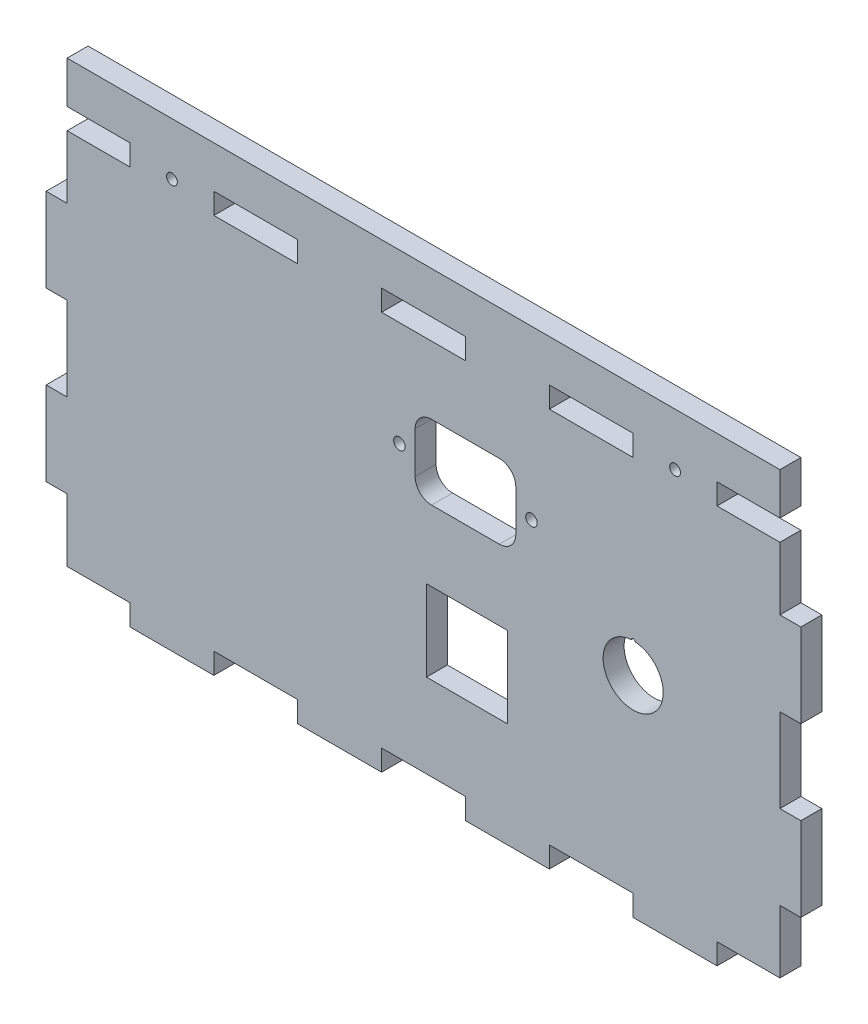
SolidWorks part; units mm, degrees
ref_plane "Front Plane" through (0, 0, 0) normal (0, 0, 1) x (1, 0, 0)
ref_plane "Top Plane" through (0, 0, 0) normal (0, 1, 0) x (1, 0, 0)
ref_plane "Right Plane" through (0, 0, 0) normal (1, 0, 0) x (0, 0, -1)
sketch "Sketch1" plane through (0, 0, 0) normal (0, 0, 1) x (1, 0, 0)
  line L1 (0, 0) -> (228.6, 0)
  line L2 (0, 0) -> (0, 139.7)
  line L3 (0, 139.7) -> (228.6, 139.7)
  line L4 (228.6, 0) -> (228.6, 139.7)
  dimension "D1" = 228.6
  dimension "D2" = 139.7
extrude "Boss-Extrude1" add sketch "Sketch1" along normal blind 6.35
sketch "Sketch5" plane through (0, 0, 6.35) normal (0, 0, 1) x (1, 0, 0)
  line L1 (0, 0) -> (6.35, 0)
  line L2 (0, 0) -> (0, 25.4)
  line L3 (0, 25.4) -> (6.35, 25.4)
  line L4 (6.35, 0) -> (6.35, 25.4)
  dimension "D1" = 25.4
  dimension "D2" = 6.35
extrude "Cut-Extrude4" cut sketch "Sketch5" against normal blind 6.35
sketch "Sketch6" plane through (0, 0, 6.35) normal (0, 0, 1) x (1, 0, 0)
  line L1 (0, 0) -> (25.4, 0)
  line L2 (0, 0) -> (0, 6.35)
  line L3 (0, 6.35) -> (25.4, 6.35)
  line L4 (25.4, 0) -> (25.4, 6.35)
  dimension "D1" = 6.35
  dimension "D2" = 25.4
extrude "Cut-Extrude5" cut sketch "Sketch6" against normal blind 6.35
pattern_linear "LPattern5" count 3 spacing 50.8 along (0, 1, 0) count 2 spacing 222.25 along (1, 0, 0) of "Cut-Extrude4"
pattern_linear "LPattern6" count 5 spacing 50.8 along (1, 0, 0) count 2 spacing 120.65 along (0, 1, 0) of "Cut-Extrude5"
sketch "Sketch7" plane through (0, 0, 6.35) normal (0, 0, 1) x (1, 0, 0)
  line L1 (6.35, 120.65) -> (0, 120.65)
  line L2 (6.35, 120.65) -> (6.35, 139.7)
  line L3 (6.35, 139.7) -> (0, 139.7)
  line L4 (0, 120.65) -> (0, 139.7)
  dimension "D1" = 6.35
  dimension "D2" = 19.05
extrude "Cut-Extrude6" cut sketch "Sketch7" against normal blind 6.35
sketch "Sketch8" plane through (0, 0, 6.35) normal (0, 0, 1) x (1, 0, 0)
  line L1 (228.6, 139.7) -> (222.25, 139.7)
  line L2 (228.6, 139.7) -> (228.6, 120.65)
  line L3 (228.6, 120.65) -> (222.25, 120.65)
  line L4 (222.25, 139.7) -> (222.25, 120.65)
extrude "Cut-Extrude7" cut sketch "Sketch8" against normal blind 6.35
hole_wizard "#4 Clearance Hole1" positions "Sketch10" profile "Sketch9" hole size "#4" standard "ANSI Inch"
sketch "Sketch10" plane through (0, 0, 6.35) normal (0, 0, 1) x (1, 0, 0)
  line L0 (203.2, 127) -> (203.2, 120.65) construction
  line L1 (222.25, 127) -> (203.2, 127) construction
  line L2 (25.4, 120.65) -> (25.4, 127) construction
  line L3 (76.2, 127) -> (50.8, 127) construction
  point P0 (38.1, 123.825)
  point P2 (190.5, 123.825)
  point P7 (203.2, 123.825)
  point P10 (25.4, 123.825)
  dimension "D1" = 12.7
  dimension "D2" = 3.175
  dimension "D3" = 12.7
  dimension "D4" = 3.175
sketch "Sketch9" plane through (38.1, 123.825, 6.35) normal (1, 0, 0) x (0, -1, 0)
  line L0 (0, 0) -> (0, 11.1406)
  line L1 (0, 11.1406) -> (1.6319, 10.16)
  line L2 (1.6319, 10.16) -> (1.6319, 0)
  line L5 (1.6319, 0) -> (0, 0)
  line L10 (0, 11.1406) -> (-1.6319, 10.16) construction
  line L11 (0, -6.35) -> (0, 107.95) construction
  dimension "Hole Dia." = 3.2639
  dimension "Hole Depth" = 10.16
  dimension "Drill Angle" = 118
sketch "Sketch11" plane through (0, 0, 6.35) normal (0, 0, 1) x (1, 0, 0)
  line L0 (228.6, 76.2) -> (228.6, 101.6) construction
  line L1 (177.8, 0) -> (203.2, 0) construction
  circle A0 centre (177.8, 63.5) radius 9.1
  circle A1 centre (177.8, 72.6) radius 0.55
  dimension "D1" = 18.2
  dimension "D2" = 50.8
  dimension "D3" = 63.5
  dimension "D4" = 1.1
extrude "Cut-Extrude8" cut sketch "Sketch11" against normal blind 6.35 contours A1 A0
sketch "Sketch12" plane through (0, 0, 6.35) normal (0, 0, 1) x (1, 0, 0)
  line L0 (228.6, 76.2) -> (228.6, 101.6) construction
  line L1 (116.75, 100.15) -> (137.25, 100.15)
  line L2 (111.75, 95.15) -> (111.75, 82.65)
  line L3 (116.75, 77.65) -> (137.25, 77.65)
  line L4 (142.25, 95.15) -> (142.25, 82.65)
  line L5 (222.25, 139.7) -> (6.35, 139.7) construction
  circle A0 centre (107, 88.9) radius 1.75
  circle A1 centre (147, 88.9) radius 1.75
  arc A2 (111.75, 82.65) -> (116.75, 77.65) centre (116.75, 82.65) ccw
  arc A3 (137.25, 100.15) -> (142.25, 95.15) centre (137.25, 95.15) cw
  arc A4 (137.25, 77.65) -> (142.25, 82.65) centre (137.25, 82.65) ccw
  arc A5 (111.75, 95.15) -> (116.75, 100.15) centre (116.75, 95.15) cw
  point P8 (142.25, 88.9)
  point P9 (127, 100.15)
  point P18 (142.25, 100.15)
  point P21 (142.25, 77.65)
  point P24 (111.75, 100.15)
  dimension "D1" = 3.5
  dimension "D2" = 3.5
  dimension "D10" = 5
  dimension "D11" = 5
  dimension "D12" = 5
  dimension "D13" = 5
  dimension "D3" = 40
  dimension "D4" = 30.5
  dimension "D5" = 22.5
  dimension "D6" = 0
  dimension "D7" = 20
  dimension "D8" = 101.6
  dimension "D9" = 50.8
extrude "Cut-Extrude9" cut sketch "Sketch12" against normal blind 6.35
sketch "Sketch13" plane through (0, 0, 6.35) normal (0, 0, 1) x (1, 0, 0)
  line L0 (228.6, 25.4) -> (228.6, 50.8) construction
  line L1 (115.2, 56.25) -> (139.7, 56.25)
  line L2 (115.2, 56.25) -> (115.2, 31.75)
  line L3 (115.2, 31.75) -> (139.7, 31.75)
  line L4 (139.7, 56.25) -> (139.7, 31.75)
  line L5 (127, 0) -> (152.4, 0) construction
  dimension "D1" = 24.5
  dimension "D2" = 24.5
  dimension "D3" = 88.9
  dimension "D4" = 31.75
extrude "Cut-Extrude10" cut sketch "Sketch13" against normal blind 6.35
